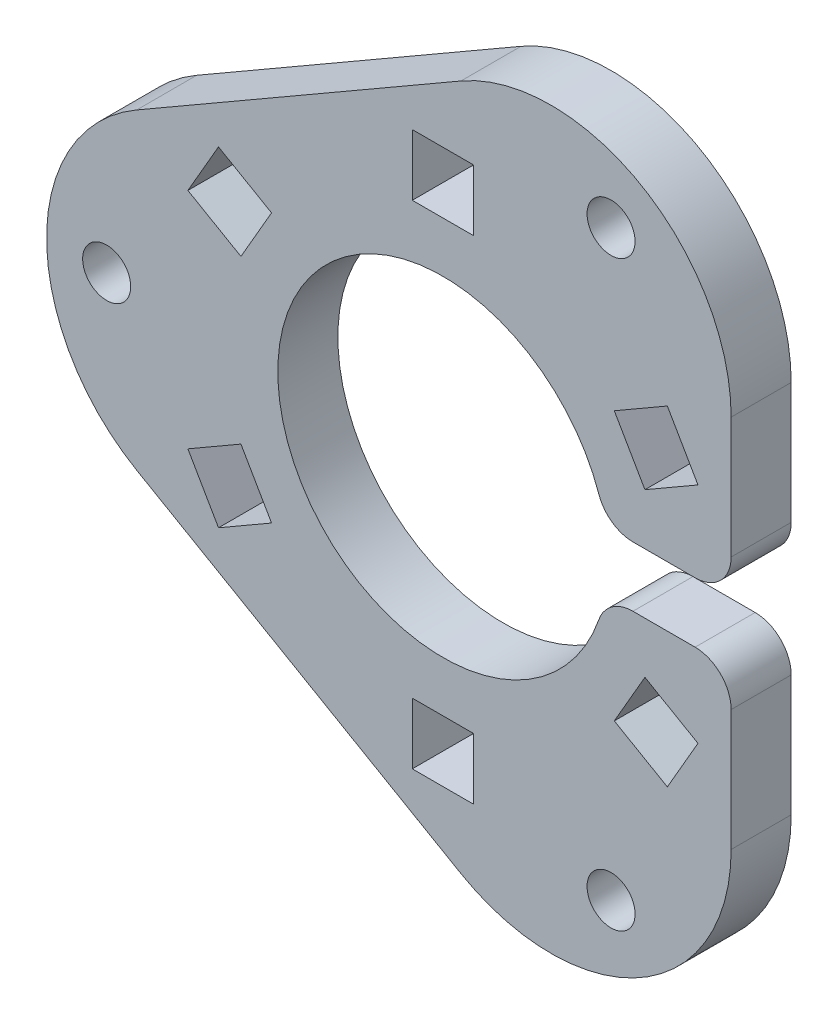
SolidWorks part; units mm, degrees
ref_plane "Front Plane" through (0, 0, 0) normal (0, 0, 1) x (1, 0, 0)
ref_plane "Top Plane" through (0, 0, 0) normal (0, 1, 0) x (1, 0, 0)
ref_plane "Right Plane" through (0, 0, 0) normal (1, 0, 0) x (0, 0, -1)
sketch "Sketch1" plane through (0, 0, 0) normal (0, 0, 1) x (1, 0, 0)
  line L0 (-26, 0) -> (26, 0) construction
  line L7 (-2.55, 23.05) -> (2.55, 23.05)
  line L8 (-2.55, 23.05) -> (-2.55, 17.95)
  line L9 (-2.55, 17.95) -> (2.55, 17.95)
  line L10 (2.55, 23.05) -> (2.55, 17.95)
  line L23 (0, 26) -> (0, -26) construction
  line L24 (21.2369, 9.3166) -> (16.8202, 6.7666)
  line L25 (14.2702, 11.1834) -> (16.8202, 6.7666)
  line L26 (18.6869, 13.7334) -> (14.2702, 11.1834)
  line L27 (18.6869, 13.7334) -> (21.2369, 9.3166)
  line L28 (18.6869, -13.7334) -> (14.2702, -11.1834)
  line L29 (16.8202, -6.7666) -> (14.2702, -11.1834)
  line L30 (21.2369, -9.3166) -> (16.8202, -6.7666)
  line L31 (21.2369, -9.3166) -> (18.6869, -13.7334)
  line L32 (-2.55, -23.05) -> (-2.55, -17.95)
  line L33 (2.55, -17.95) -> (-2.55, -17.95)
  line L34 (2.55, -23.05) -> (2.55, -17.95)
  line L35 (2.55, -23.05) -> (-2.55, -23.05)
  line L36 (-21.2369, -9.3166) -> (-16.8202, -6.7666)
  line L37 (-14.2702, -11.1834) -> (-16.8202, -6.7666)
  line L38 (-18.6869, -13.7334) -> (-14.2702, -11.1834)
  line L39 (-18.6869, -13.7334) -> (-21.2369, -9.3166)
  line L40 (-18.6869, 13.7334) -> (-14.2702, 11.1834)
  line L41 (-16.8202, 6.7666) -> (-14.2702, 11.1834)
  line L42 (-21.2369, 9.3166) -> (-16.8202, 6.7666)
  line L43 (-21.2369, 9.3166) -> (-18.6869, 13.7334)
  line L44 (24, 2.5) -> (13.5208, 2.5)
  line L45 (24, -2.5) -> (13.5208, -2.5)
  line L46 (24, 41.5692) -> (24, -41.5692) construction
  line L47 (24, -41.5692) -> (-48, 0) construction
  line L48 (-48, 0) -> (24, 41.5692) construction
  line L49 (24, 2.5) -> (24, 41.5692)
  line L50 (24, 41.5692) -> (-48, 0)
  line L51 (-48, 0) -> (24, -41.5692)
  line L52 (24, -41.5692) -> (24, -2.5)
  line L53 (0, 0) -> (24, 41.5692) construction
  line L54 (-2.55, 20.5) -> (2.55, 20.5) construction
  circle A0 centre (0, 0) radius 13.75 construction
  arc A2 (13.5208, 2.5) -> (13.5208, -2.5) centre (0, 0) ccw
  circle A4 centre (14, 24.2487) radius 2
  circle A5 centre (14, -24.2487) radius 2
  circle A6 centre (-28, 0) radius 2
  point P40 (0, 0)
  point P48 (0, 0)
  point P50 (0, 0)
  dimension "D2" = 24
  dimension "D1" = 27.5
  dimension "D10" = 4
  dimension "D3" = 5.1
  dimension "D4" = 5.1
  dimension "D5" = 20.5
  dimension "D6" = 6
  dimension "D7" = 5
  dimension "D9" = 28
  dimension "D11" = 3
  dimension "D8" = 3
extrude "Boss-Extrude1" add sketch "Sketch1" along normal blind 5
fillet "Congé1" radius 15 3 edges at (24, -41.5692, 2.5) (-48, 0, 2.5) (24, 41.5692, 2.5)
fillet "Congé2" radius 3 4 edges at (13.5208, 2.5, 2.5) (13.5208, -2.5, 2.5) (24, -2.5, 2.5) (24, 2.5, 2.5)
